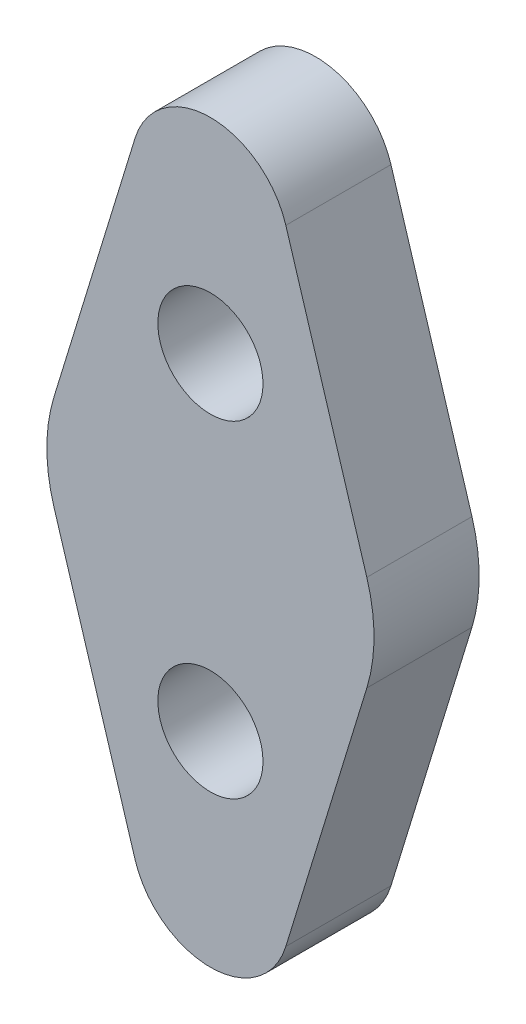
SolidWorks part; units mm, degrees
ref_plane "Alzado" through (0, 0, 0) normal (0, 0, 1) x (1, 0, 0)
ref_plane "Planta" through (0, 0, 0) normal (0, 1, 0) x (1, 0, 0)
ref_plane "Vista lateral" through (0, 0, 0) normal (1, 0, 0) x (0, 0, -1)
sketch "Croquis2" plane through (0, 0, 0) normal (0, 0, 1) x (1, 0, 0)
  line L0 (0, 35) -> (0, -35) construction
  line L1 (-14.8732, 4.5567) -> (-7.171, 29.697)
  line L2 (7.171, 29.697) -> (14.8732, 4.5567)
  line L3 (-14.8732, -4.5567) -> (-7.171, -29.697)
  line L4 (14.8732, -4.5567) -> (7.171, -29.697)
  circle A0 centre (0, 0) radius 15.5556 construction
  arc A1 (7.171, 29.697) -> (-7.171, 29.697) centre (0, 27.5) ccw
  arc A2 (-7.171, -29.697) -> (7.171, -29.697) centre (0, -27.5) ccw
  arc A3 (-14.8732, -4.5567) -> (-14.8732, 4.5567) centre (0, 0) cw
  arc A4 (14.8732, 4.5567) -> (14.8732, -4.5567) centre (0, 0) cw
  circle A5 centre (0, 15.5556) radius 5
  circle A6 centre (0, -15.5556) radius 5
  point P2 (0, 0)
  dimension "D2" = 31.1111
  dimension "D3" = 7.5
  dimension "D4" = 10
  dimension "D1" = 70
extrude "Saliente-Extruir2" add sketch "Croquis2" along normal blind 10
